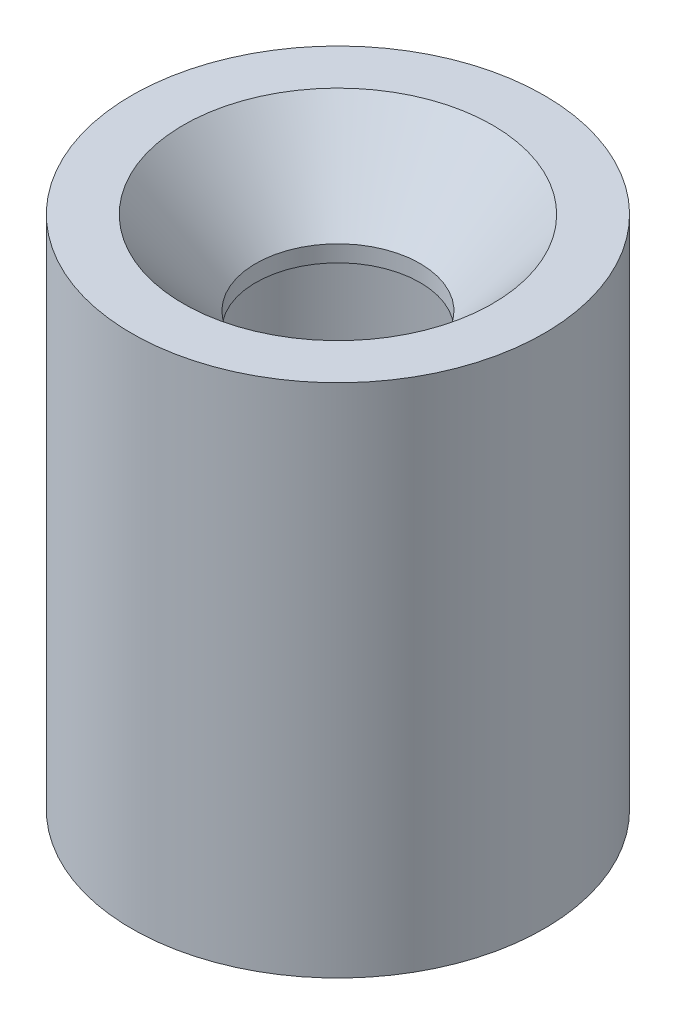
SolidWorks part; units mm, degrees
ref_plane "Front Plane" through (0, 0, 0) normal (0, 0, 1) x (1, 0, 0)
ref_plane "Top Plane" through (0, 0, 0) normal (0, 1, 0) x (1, 0, 0)
ref_plane "Right Plane" through (0, 0, 0) normal (1, 0, 0) x (0, 0, -1)
sketch "Sketch1" plane through (0, 0, 0) normal (0, 0, 1) x (1, 0, 0)
  line L0 (6.35, 0) -> (6.35, 15.875)
  line L1 (6.35, 15.875) -> (4.7625, 15.875)
  line L2 (4.7625, 15.875) -> (2.5273, 13.3037)
  line L3 (2.5273, 13.3037) -> (2.5273, 12.7957)
  line L4 (2.5273, 12.7957) -> (4.9022, 12.7957)
  line L5 (4.9022, 12.7957) -> (4.9022, 0)
  line L6 (4.9022, 0) -> (6.35, 0)
  line L7 (0, 0) -> (0, 19.9576) construction
  dimension "D1" = 4.9022
  dimension "D2" = 15.875
  dimension "D3" = 6.35
  dimension "D4" = 0.508
  dimension "D5" = 4.7625
  dimension "D6" = 41
  dimension "D7" = 2.5273
revolve "Revolve1" add sketch "Sketch1" angle 360 about L7
